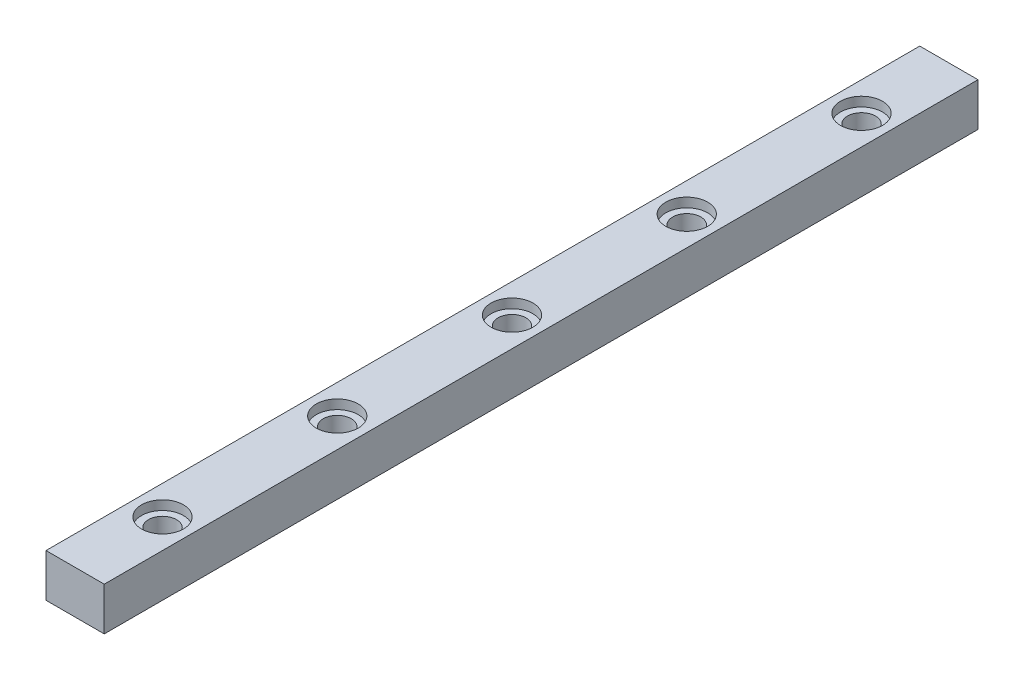
SolidWorks part; units mm, degrees
material "AISI 304"
ref_plane "前视基准面" through (0, 0, 0) normal (0, 0, 1) x (1, 0, 0)
ref_plane "上视基准面" through (0, 0, 0) normal (0, 1, 0) x (1, 0, 0)
ref_plane "右视基准面" through (0, 0, 0) normal (1, 0, 0) x (0, 0, -1)
other "Configuration Table"
sketch "草图1" plane through (0, 0, 0) normal (0, 0, 1) x (1, 0, 0)
  line L1 (-2.5, -1.85) -> (2.5, -1.85)
  line L2 (-2.5, -1.85) -> (-2.5, 1.85)
  line L3 (-2.5, 1.85) -> (2.5, 1.85)
  line L4 (2.5, -1.85) -> (2.5, 1.85)
  line L5 (-2.5, -1.85) -> (2.5, 1.85) construction
  line L6 (-2.5, 1.85) -> (2.5, -1.85) construction
  point P0 (0, 0)
  dimension "D1" = 3.7
  dimension "D2" = 5
extrude "凸台-拉伸1" add sketch "草图1" along normal mid plane 75
sketch "草图2" plane through (0, 1.85, 0) normal (0, 1, 0) x (1, 0, 0)
  line L0 (0, -37.5) -> (0, -30) construction
  line L1 (2.5, -37.5) -> (-2.5, -37.5) construction
  circle A0 centre (0, -30) radius 1.2
  dimension "D2" = 2.4
  dimension "D1" = 7.5
extrude "切除-拉伸1" cut sketch "草图2" against normal mid plane 6021
sketch "草图3" plane through (0, 1.85, 0) normal (0, 1, 0) x (1, 0, 0)
  circle A0 centre (0, -30) radius 1.8
  dimension "D1" = 3.6
extrude "切除-拉伸2" cut sketch "草图3" against normal blind 0.8
pattern_linear "阵列(线性)1" count 5 spacing 15 along (0, 0, -1) of "切除-拉伸2", "切除-拉伸1"
